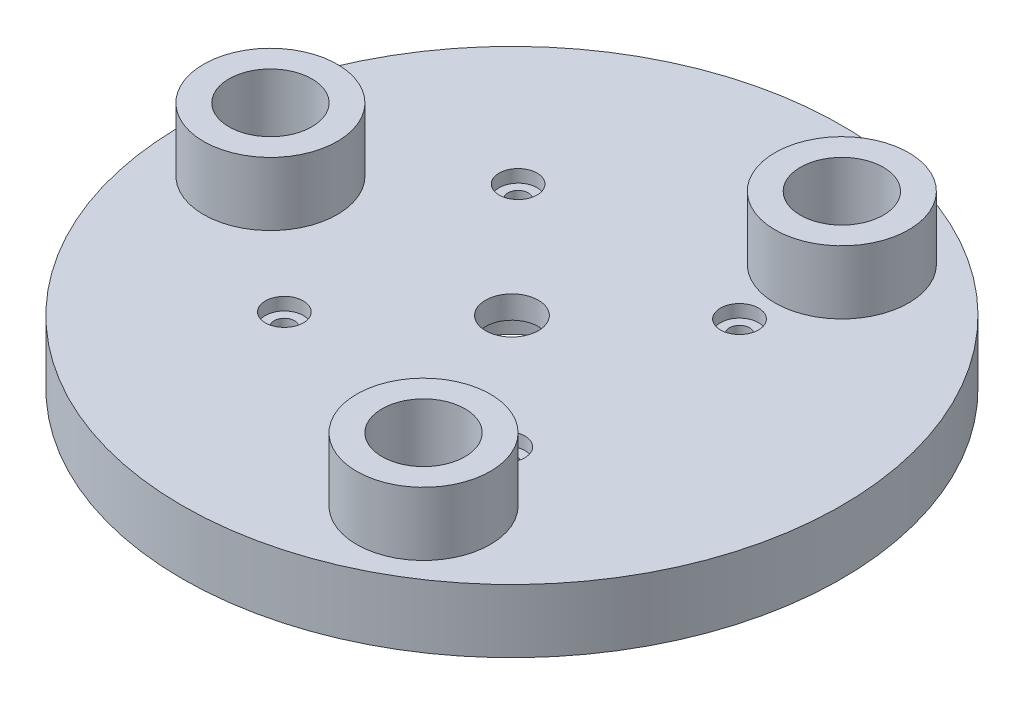
SolidWorks part; units mm, degrees
ref_plane "Front Plane" through (0, 0, 0) normal (0, 0, 1) x (1, 0, 0)
ref_plane "Top Plane" through (0, 0, 0) normal (0, 1, 0) x (1, 0, 0)
ref_plane "Right Plane" through (0, 0, 0) normal (1, 0, 0) x (0, 0, -1)
sketch "Sketch2" plane through (0, 0, 0) normal (0, 1, 0) x (1, 0, 0)
  circle A0 centre (0, 0) radius 26
  circle A1 centre (0, 0) radius 2.0856
  point P11 (0, 0)
  dimension "D1" = 52
extrude "Boss-Extrude2" add sketch "Sketch2" along normal blind 10
sketch "Sketch3" plane through (0, 10, 0) normal (0, -1, 0) x (1, 0, 0)
  circle A3 centre (9.5263, -16.4999) radius 3.275
  circle A4 centre (9.5263, 16.4999) radius 3.275
  circle A5 centre (-19.0525, 0) radius 3.275
  circle A6 centre (9.5263, -16.4999) radius 3.175 construction
  circle A7 centre (-19.0525, 0) radius 3.175 construction
  circle A8 centre (9.5263, 16.4999) radius 3.175 construction
  dimension "D1" = 6.55
  dimension "D2" = 6.55
  dimension "D3" = 6.55
extrude "Cut-Extrude1" cut sketch "Sketch3" along normal blind 7.5
sketch "Sketch4" plane through (0, 10, 0) normal (0, 1, 0) x (1, 0, 0)
  arc A23 (-13.7775, 0) -> (-13.7775, 0) centre (-19.0525, 0) ccw
  circle A24 centre (-19.0525, 0) radius 5.275
  arc A30 (14.8013, -16.4999) -> (14.8013, -16.4999) centre (9.5263, -16.4999) ccw
  circle A31 centre (9.5263, -16.4999) radius 5.275
  circle A32 centre (0, 0) radius 26 construction
  arc A33 (14.8012, 16.4999) -> (14.8012, 16.4999) centre (9.5263, 16.4999) ccw
  circle A34 centre (9.5263, 16.4999) radius 5.275
  circle A35 centre (0, 0) radius 26
  dimension "D1" = 2
  dimension "D2" = 2
  dimension "D3" = 2
extrude "Cut-Extrude2" cut sketch "Sketch4" against normal blind 5
sketch "Sketch5" plane through (0, 0, 0) normal (0, -1, 0) x (1, 0, 0)
  line L4 (4.064, -4.065) -> (-4.064, 4.065) construction
  line L5 (-4.064, -4.065) -> (4.064, 4.065) construction
  circle A1 centre (0, 0) radius 5.25
  point P1 (0, 0)
  dimension "D3" = 10.5
  dimension "D1" = 8.13
  dimension "D2" = 8.128
extrude "Cut-Extrude3" cut sketch "Sketch5" against normal blind 3.2
sketch "Sketch6" plane through (0, 5, 0) normal (0, 1, 0) x (1, 0, 0)
  circle A0 centre (-8.7331, 9.2208) radius 0.8
  circle A1 centre (9.2208, 8.7331) radius 0.8
  circle A2 centre (8.7331, -9.2208) radius 0.8
  circle A3 centre (-9.2208, -8.7331) radius 0.8
  point P12 (0, 0)
  dimension "D1" = 12.7
  dimension "D2" = 4
extrude "Cut-Extrude4" cut sketch "Sketch6" against normal through all both and the other way through all
sketch "Sketch7" plane through (0, 5, 0) normal (0, 1, 0) x (1, 0, 0)
  circle A0 centre (-8.7331, 9.2208) radius 1.5
  circle A1 centre (9.2208, 8.7331) radius 1.5
  circle A2 centre (8.7331, -9.2208) radius 1.5
  circle A3 centre (-9.2208, -8.7331) radius 1.5
  point P12 (0, 0)
  dimension "D1" = 4
  dimension "D2" = 3
extrude "Cut-Extrude5" cut sketch "Sketch7" against normal blind 1
